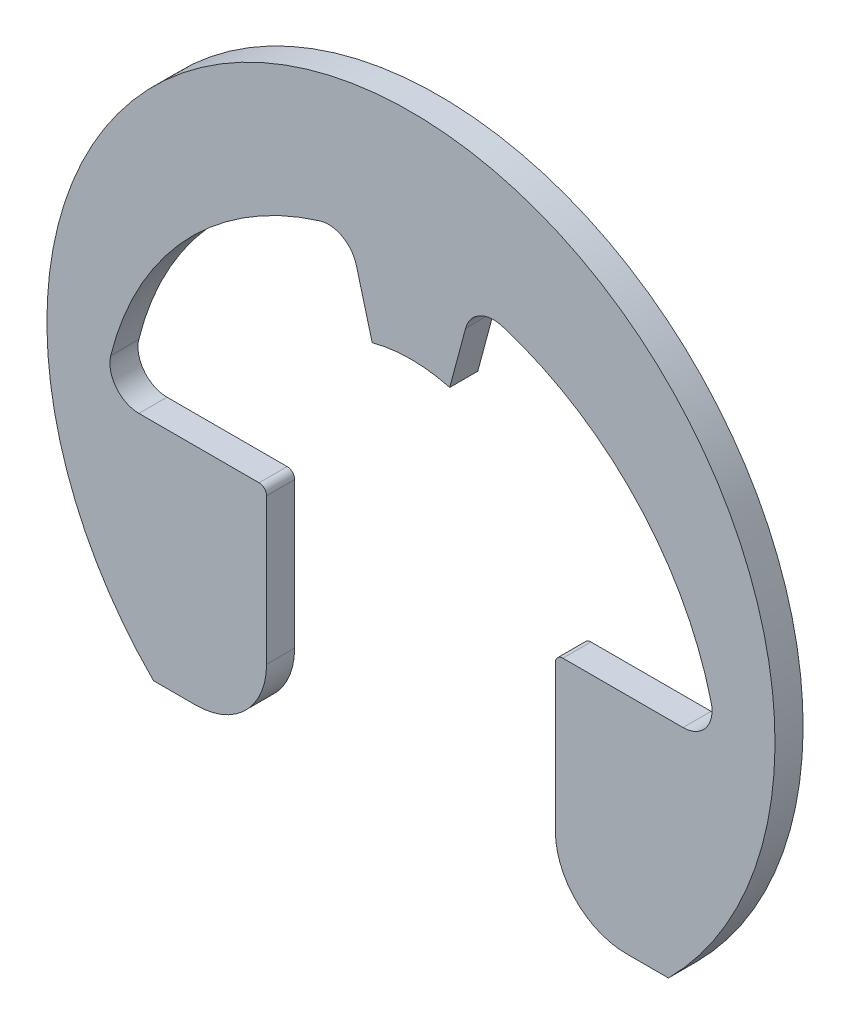
SolidWorks part; units mm, degrees
ref_plane "Plane1" through (0, 0, 0) normal (0, 0, 1) x (1, 0, 0)
ref_plane "Plane2" through (0, 0, 0) normal (0, 1, 0) x (1, 0, 0)
ref_plane "Plane3" through (0, 0, 0) normal (1, 0, 0) x (0, 0, -1)
sketch "Clipboard" plane through (0, 0, 0) normal (0, 0, 1) x (1, 0, 0)
  line L0 (0, 0) -> (2.7, 0)
  circle A0 centre (0, 0) radius 3.075
  circle A1 centre (0, 0) radius 7.475
  dimension "FreeID" = 6.15
  dimension "FreeOD" = 14.95
  dimension "LargeSection" = 2.7
sketch "BodySke" plane through (0, 0, 0) normal (0, 0, 1) x (1, 0, 0)
  line L0 (-6.4289, 0) -> (6.4289, 0) construction
  line L1 (0, 0) -> (0, 5.0789) construction
  line L2 (0, 0) -> (0.1962, 0.7323) construction
  line L3 (0, 0) -> (7.5138, -2.0133) construction
  line L4 (0, 0) -> (-0.1962, 0.7323) construction
  line L5 (0, 0) -> (-7.5138, -2.0133) construction
  line L6 (0, 0) -> (5.5005, -5.5005) construction
  line L7 (0, 0) -> (-5.5005, -5.5005) construction
  line L8 (5.5005, -5.5005) -> (4.5965, -5.5005)
  line L9 (-4.5965, -5.5005) -> (-5.5005, -5.5005)
  line L10 (3.2455, -0.7096) -> (5.8126, -0.7096)
  line L11 (1.1664, 4.3532) -> (0.8282, 3.091)
  line L12 (-1.1664, 4.3532) -> (-0.8282, 3.091)
  line L13 (3.0855, -0.8696) -> (3.0855, -3.9895)
  line L14 (-3.2455, -0.7096) -> (-5.8126, -0.7096)
  line L15 (-3.0855, -0.8696) -> (-3.0855, -3.9895)
  circle A0 centre (0, 0) radius 3.2 construction
  arc A1 (6.4289, 0) -> (-6.4289, 0) centre (0, -1.5294) ccw construction
  arc A2 (5.5005, -5.5005) -> (-5.5005, -5.5005) centre (0, 0) ccw
  arc A3 (3.2455, -0.7096) -> (3.0855, -0.8696) centre (3.2455, -0.8696) ccw
  arc A4 (-3.0855, -0.8696) -> (-3.2455, -0.7096) centre (-3.2455, -0.8696) ccw
  arc A5 (-6.4144, 0.0595) -> (-1.9481, 4.7852) centre (0, -1.5294) cw
  arc A6 (-0.8282, 3.091) -> (0.8282, 3.091) centre (0, 0) cw
  arc A7 (1.9481, 4.7852) -> (6.4144, 0.0595) centre (0, -1.5294) cw
  arc A8 (5.8126, -0.7096) -> (6.4144, 0.0595) centre (5.8126, -0.0896) ccw
  arc A9 (1.9481, 4.7852) -> (1.1664, 4.3532) centre (1.7653, 4.1927) ccw
  arc A10 (-1.1664, 4.3532) -> (-1.9481, 4.7852) centre (-1.7653, 4.1927) ccw
  arc A11 (-6.4144, 0.0595) -> (-5.8126, -0.7096) centre (-5.8126, -0.0896) ccw
  arc A12 (3.0855, -3.9895) -> (4.5965, -5.5005) centre (4.5965, -3.9895) ccw
  arc A13 (-4.5965, -5.5005) -> (-3.0855, -3.9895) centre (-4.5965, -3.9895) ccw
  dimension "GrooveDia" = 6.4
  dimension "OutsideDia" = 15.5577
  dimension "InnerTipRad" = 0.16
  dimension "CavityFilletRad" = 0.62
  dimension "OuterTipRadius" = 1.511
  dimension "D3" = 30
  dimension "D1" = 15
  dimension "CavityWidth" = 12.8577
  dimension "CavityHeight" = 5.0789
extrude "Body" add sketch "BodySke" against normal blind 0.6
equation "' \"FreeID@Clipboard\" = 2.9"
equation "' \"Thickness@Body\" = 0.6"
equation "' \"GrooveDia@BodySke\" = 3.0"
equation "' \"FreeOD@Clipboard\" = 8.5"
equation "' \"LargeSection@Clipboard\" = 1.5"
equation "' \"FreeID@Clipboard\" = 11.5"
equation "' \"Thickness@Body\" = 1.1"
equation "' \"GrooveDia@BodySke\" = 11.8"
equation "' \"FreeOD@Clipboard\" = 23.2"
equation "' \"LargeSection@Clipboard\" = 3.9"
equation "\"OutsideDia@BodySke\" = ( \"GrooveDia@BodySke\"  /  \"FreeID@Clipboard\" )  * \"FreeOD@Clipboard\""
equation "\"CavityHeight@BodySke\" = \"OutsideDia@BodySke\"  /  2 - \"LargeSection@Clipboard\""
equation "\"CavityWidth@BodySke\" = \"OutsideDia@BodySke\" -  \"LargeSection@Clipboard\""
equation "\"CavityFilletRad@BodySke\" =  (\"CavityHeight@BodySke\" * 2 - \"GrooveDia@BodySke\") / 2 * 0.33"
equation "\"InnerTipRad@BodySke\" = \"GrooveDia@BodySke\" * 0.025"
equation "\"OuterTipRadius@BodySke\" =  (\"OutsideDia@BodySke\" - \"GrooveDia@BodySke\") / 2 * 0.33"
